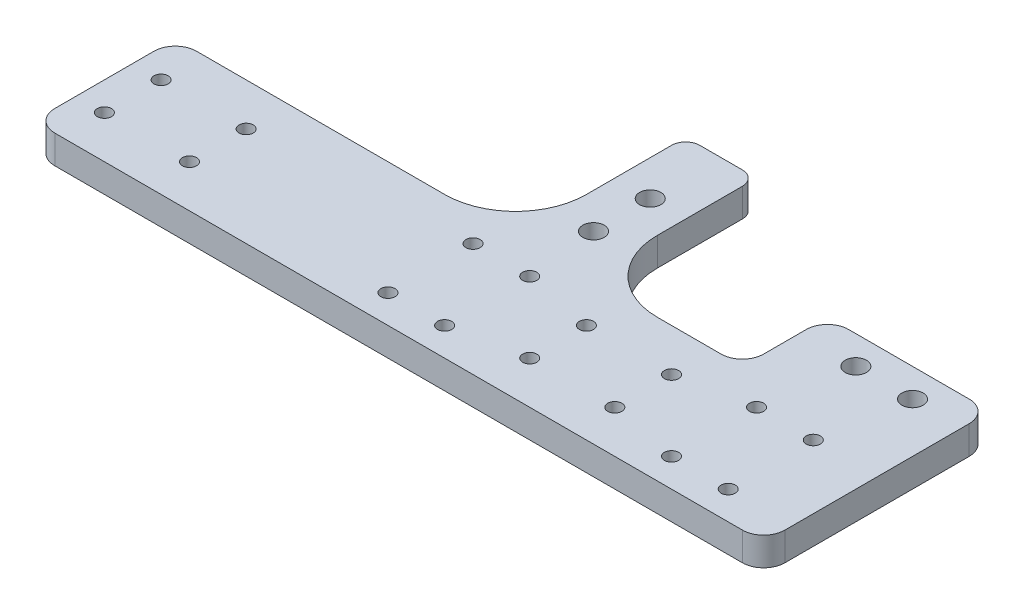
SolidWorks part; units mm, degrees
material "Thornel Mat VMA"
ref_plane "前视基准面" through (0, 0, 0) normal (0, 0, 1) x (1, 0, 0)
ref_plane "上视基准面" through (0, 0, 0) normal (0, 1, 0) x (1, 0, 0)
ref_plane "右视基准面" through (0, 0, 0) normal (1, 0, 0) x (0, 0, -1)
other "Configuration Table"
sketch "草图1" plane through (0, 0, 0) normal (0, 1, 0) x (1, 0, 0)
  line L0 (0, 0) -> (0, 20.1669) construction
  line L1 (-40, -10) -> (40, -10)
  line L2 (-40, -10) -> (-40, 10)
  line L3 (-40, 10) -> (40, 10)
  line L4 (40, -10) -> (40, 10)
  line L5 (-40, -10) -> (40, 10) construction
  line L6 (-40, 10) -> (40, -10) construction
  line L7 (0, 0) -> (39.3199, 0) construction
  line L8 (10, 0) -> (10, 19.4616) construction
  line L9 (30, 0) -> (30, 22.3006) construction
  line L10 (40, 10) -> (63, 10)
  line L11 (63, 10) -> (63, -10)
  line L12 (63, -10) -> (40, -10)
  line L13 (40, 10) -> (40, 22)
  line L14 (40, 22) -> (63, 22)
  line L15 (63, 22) -> (63, 10)
  circle A0 centre (6, 6) radius 1
  circle A1 centre (14, 6) radius 1
  circle A2 centre (14, -6) radius 1
  circle A3 centre (6, -6) radius 1
  circle A4 centre (24, 4) radius 1
  circle A5 centre (36, 4) radius 1
  circle A6 centre (36, -4) radius 1
  circle A7 centre (24, -4) radius 1
  circle A8 centre (-24, -4) radius 1
  circle A9 centre (-36, -4) radius 1
  circle A10 centre (-36, 4) radius 1
  circle A11 centre (-24, 4) radius 1
  circle A16 centre (46, 6) radius 1
  circle A17 centre (46, -6) radius 1
  circle A18 centre (54, -6) radius 1
  circle A19 centre (54, 6) radius 1
  circle A22 centre (48, 18) radius 1.5
  circle A23 centre (56, 18) radius 1.5
  point P0 (0, 0)
  dimension "D3" = 2
  dimension "D4" = 8
  dimension "D5" = 12
  dimension "D7" = 2
  dimension "D8" = 12
  dimension "D9" = 8
  dimension "D13" = 46
  dimension "D14" = 12
  dimension "D15" = 3
  dimension "D16" = 3
  dimension "D17" = 8
  dimension "D18" = 4
  dimension "D19" = 4
  dimension "D20" = 7
  dimension "D1" = 80
  dimension "D2" = 20
  dimension "D6" = 10
  dimension "D10" = 30
  dimension "D11" = 23
  dimension "D12" = 2
extrude "凸台-拉伸1" add sketch "草图1" along normal blind 4 contours L1 L4 L3 L2 A9 A8 A5 A4 A1 A0 A2 A3 A6 A7 A10 A11 | L12 L11 L10 L4 A17 A16 A18 A19 | L15 L14 L13 L10 A23 A22
fillet "圆角1" radius 3 6 edges at (-40, 2, -10) (-40, 2, 10) (63, 2, 10) (63, 2, -22) (40, 2, -22) (40, 2, -10)
sketch "草图2" plane through (0, 4, 0) normal (0, 1, 0) x (1, 0, 0)
  line L0 (8, 10) -> (8, 34)
  line L1 (-37, 10) -> (37, 10) construction
  line L2 (8, 34) -> (18, 34)
  line L3 (18, 34) -> (18, 10)
  line L4 (18, 10) -> (8, 10)
  line L5 (0, 0) -> (0, 47.4408) construction
  circle A0 centre (13, 24) radius 1.5
  circle A1 centre (13, 16) radius 1.5
  dimension "D3" = 3
  dimension "D4" = 3
  dimension "D6" = 8
  dimension "D7" = 6
  dimension "D8" = 5
  dimension "D9" = 5
  dimension "D1" = 8
  dimension "D2" = 10
  dimension "D5" = 24
extrude "凸台-拉伸2" add sketch "草图2" against normal blind 4
fillet "圆角2" radius 10 2 edges at (18, 2, -10) (8, 2, -10)
fillet "圆角3" radius 2 2 edges at (18, 2, -34) (8, 2, -34)
